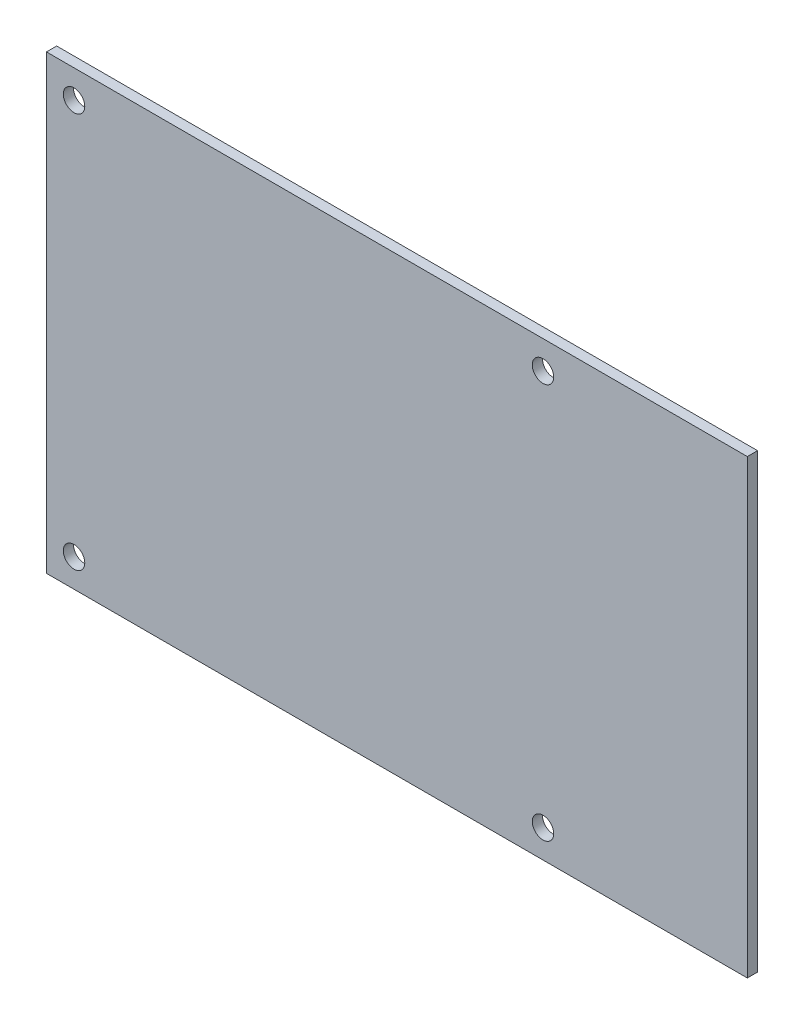
SolidWorks part; units mm, degrees
ref_plane "Front Plane" through (0, 0, 0) normal (0, 0, 1) x (1, 0, 0)
ref_plane "Top Plane" through (0, 0, 0) normal (0, 1, 0) x (1, 0, 0)
ref_plane "Right Plane" through (0, 0, 0) normal (1, 0, 0) x (0, 0, -1)
sketch "Sketch1" plane through (0, 0, 0) normal (0, 0, 1) x (1, 0, 0)
  line L0 (3.429, 52.6415) -> (3.429, 56.134) construction
  line L1 (0, 0) -> (87.122, 0)
  line L2 (0, 0) -> (0, 56.134)
  line L3 (0, 56.134) -> (87.122, 56.134)
  line L4 (87.122, 0) -> (87.122, 56.134)
  line L5 (61.722, 52.6415) -> (61.722, 56.134) construction
  line L6 (3.429, 52.6415) -> (0, 52.6415) construction
  line L7 (3.429, 3.4925) -> (3.429, 52.6415) construction
  line L8 (61.722, 3.4925) -> (61.722, 52.6415) construction
  line L9 (3.429, 52.6415) -> (61.722, 52.6415) construction
  circle A0 centre (3.429, 52.6415) radius 1.3335
  circle A1 centre (61.722, 52.6415) radius 1.3335
  circle A2 centre (61.722, 3.4925) radius 1.3335
  circle A3 centre (3.429, 3.4925) radius 1.3335
  dimension "D3" = 2.667
  dimension "D1" = 87.122
  dimension "D2" = 56.134
  dimension "D4" = 3.4925
  dimension "D5" = 3.429
  dimension "D6" = 49.149
  dimension "D7" = 58.293
extrude "Boss-Extrude1" add sketch "Sketch1" along normal blind 1.27
